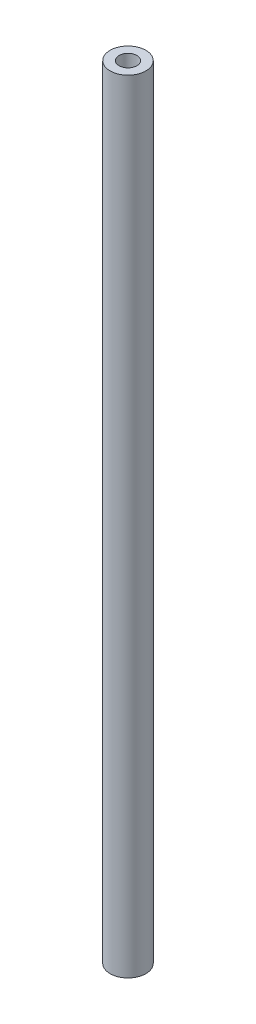
SolidWorks part; units mm, degrees
material "AISI 1045 Steel, cold drawn"
ref_plane "Front Plane" through (0, 0, 0) normal (0, 0, 1) x (1, 0, 0)
ref_plane "Top Plane" through (0, 0, 0) normal (0, 1, 0) x (1, 0, 0)
ref_plane "Right Plane" through (0, 0, 0) normal (1, 0, 0) x (0, 0, -1)
sketch "Sketch1" plane through (0, 0, 0) normal (0, 1, 0) x (1, 0, 0)
  circle A0 centre (0, 0) radius 4
  dimension "D1" = 8
extrude "Boss-Extrude1" add sketch "Sketch1" along normal blind 175
sketch "Sketch2" plane through (0, 0, 0) normal (0, -1, 0) x (1, 0, 0)
  circle A0 centre (0, 0) radius 2
  dimension "D1" = 4
extrude "Cut-Extrude1" cut sketch "Sketch2" against normal blind 30
ref_plane "Plane1" through (0, 87.5, 0) normal (0, -1, 0) x (-1, 0, 0)
mirror "Mirror1" about plane through (0, 87.5, 0) normal (0, -1, 0) of "Cut-Extrude1"
